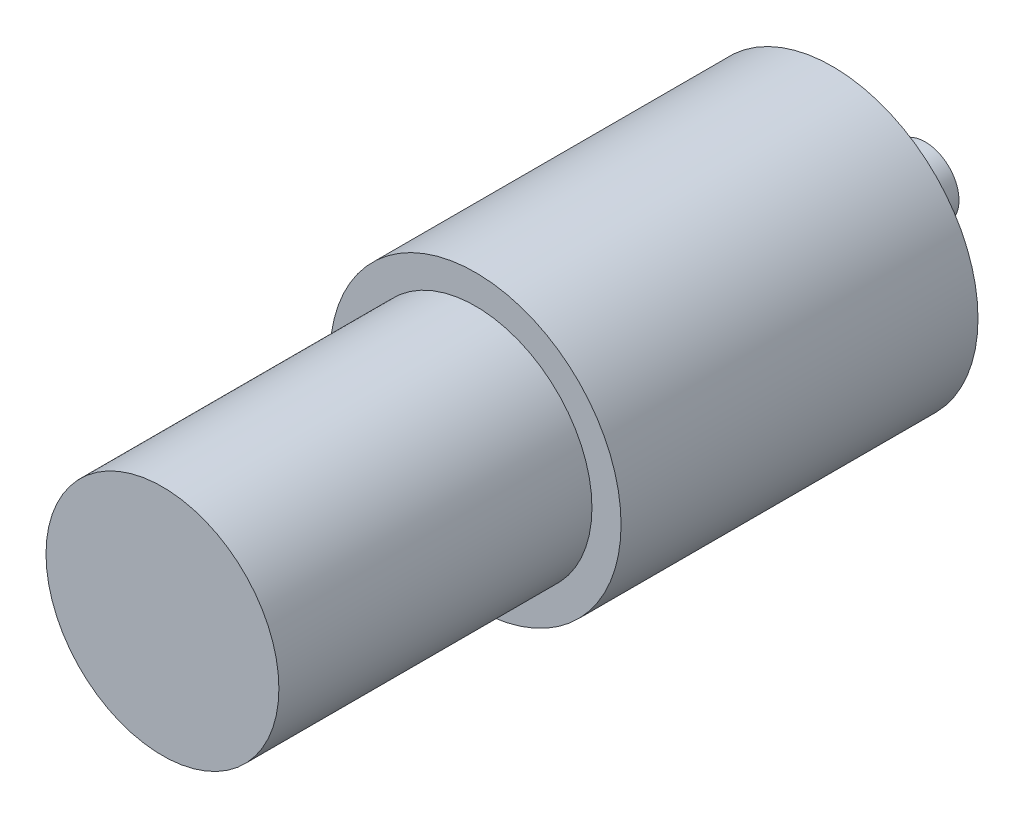
SolidWorks part; units mm, degrees
ref_plane "Alzado" through (0, 0, 0) normal (0, 0, 1) x (1, 0, 0)
ref_plane "Planta" through (0, 0, 0) normal (0, 1, 0) x (1, 0, 0)
ref_plane "Vista lateral" through (0, 0, 0) normal (1, 0, 0) x (0, 0, -1)
sketch "Sketch1" plane through (0, 0, 0) normal (0, 0, 1) x (1, 0, 0)
  circle A0 centre (0, 0) radius 17.25
  dimension "D1" = 34.5
extrude "Boss-Extrude1" add sketch "Sketch1" along normal blind 42.3
sketch "Sketch2" plane through (0, 0, 42.3) normal (0, 0, 1) x (1, 0, 0)
  circle A0 centre (0, 0) radius 13.8
  dimension "D1" = 27.6
extrude "Boss-Extrude2" add sketch "Sketch2" along normal blind 37.1
sketch "Sketch4" plane through (0, 0, 0) normal (0, 0, -1) x (-1, 0, 0)
  circle A0 centre (0, 0) radius 4
  dimension "D1" = 8
extrude "Boss-Extrude4" add sketch "Sketch4" along normal blind 11
